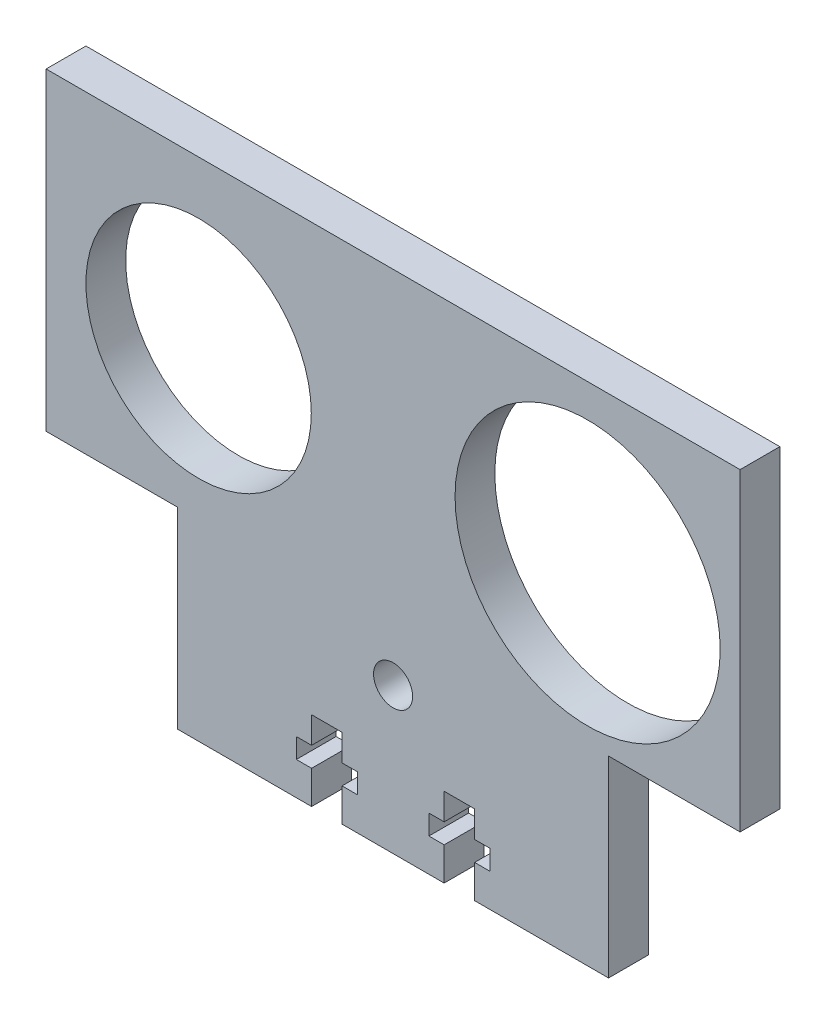
SolidWorks part; units mm, degrees
material "ABS"
ref_plane "Front Plane" through (0, 0, 0) normal (0, 0, 1) x (1, 0, 0)
ref_plane "Top Plane" through (0, 0, 0) normal (0, 1, 0) x (1, 0, 0)
ref_plane "Right Plane" through (0, 0, 0) normal (1, 0, 0) x (0, 0, -1)
sketch "Sketch1" plane through (0, 0, 0) normal (0, 0, 1) x (1, 0, 0)
  line L0 (0, 0) -> (-29.3449, 29.3449) construction
  line L1 (0, 0) -> (0, 54.3449) construction
  line L2 (-32.5, 7) -> (-32.5, -22)
  line L3 (-32.5, -22) -> (32.5, -22)
  line L4 (32.5, 7) -> (52.3449, 7)
  line L5 (0, 0) -> (0, -22) construction
  line L6 (52.3449, 7) -> (52.3449, 54.3449)
  line L7 (0, 0) -> (29.3449, 29.3449) construction
  line L10 (-32.5, 7) -> (-52.3449, 7)
  line L11 (-52.3449, 7) -> (-52.3449, 54.3449)
  line L12 (-52.3449, 54.3449) -> (52.3449, 54.3449)
  line L13 (32.5, 7) -> (32.5, -22)
  circle A0 centre (0, 0) radius 2.95
  circle A1 centre (-29.3449, 29.3449) radius 17
  circle A2 centre (29.3449, 29.3449) radius 20
  point P16 (0, 54.3449)
  dimension "D1" = 5.9
  dimension "D9" = 34
  dimension "D10" = 40
  dimension "D2" = 41.5
  dimension "D4" = 45
  dimension "D5" = 22
  dimension "D6" = 65
  dimension "D7" = 29
  dimension "D8" = 23
  dimension "D3" = 25
  dimension "D11" = 45
extrude "Boss-Extrude1" add sketch "Sketch1" along normal blind 6
sketch "Sketch3" plane through (0, 0, 6) normal (0, 0, 1) x (1, 0, 0)
  line L0 (-32.5, -22) -> (32.5, -22) construction
  line L1 (-12.3, -22) -> (-7.7, -22)
  line L2 (-12.3, -22) -> (-12.3, -17)
  line L3 (-12.3, -10) -> (-7.7, -10)
  line L4 (-7.7, -22) -> (-7.7, -17)
  line L5 (0, 0) -> (0, -22) construction
  line L6 (-7.7, -14) -> (-5.4, -14)
  line L7 (-14.6, -14) -> (-12.3, -14)
  line L8 (-14.6, -14) -> (-14.6, -17)
  line L9 (-14.6, -17) -> (-12.3, -17)
  line L10 (-5.4, -14) -> (-5.4, -17)
  line L11 (-12.3, -14) -> (-12.3, -10)
  line L12 (-7.7, -17) -> (-5.4, -17)
  line L13 (-7.7, -14) -> (-7.7, -10)
  line L14 (7.7, -14) -> (7.7, -10)
  line L15 (7.7, -17) -> (5.4, -17)
  line L16 (12.3, -14) -> (12.3, -10)
  line L17 (5.4, -14) -> (5.4, -17)
  line L18 (14.6, -17) -> (12.3, -17)
  line L19 (14.6, -14) -> (14.6, -17)
  line L20 (14.6, -14) -> (12.3, -14)
  line L21 (7.7, -14) -> (5.4, -14)
  line L22 (7.7, -22) -> (7.7, -17)
  line L23 (12.3, -10) -> (7.7, -10)
  line L24 (12.3, -22) -> (12.3, -17)
  line L25 (12.3, -22) -> (7.7, -22)
  point P6 (-10, -10)
  point P18 (-13.45, -17)
  dimension "D1" = 4.6
  dimension "D2" = 10
  dimension "D3" = 12
  dimension "D4" = 9.2
  dimension "D5" = 3
  dimension "D6" = 5
extrude "Cut-Extrude2" cut sketch "Sketch3" against normal through all
equation "\"smallPulleyTeeth\"= 15"
equation "\"largePulleyTeeth\"= 30"
equation "\"eighthThick\"= 2.9mm"
equation "\"sixteenthThick\" = 1.7mm"
equation "\"quarterThick\"=6.0mm"
equation "\"OD\" = 146mm"
equation "\"puckAngle\" = 60.5deg"
equation "\"puckDiam\" = 76.5mm"
equation "\"axlePress\" = 5.9mm"
equation "\"D1@Sketch1\"=\"axlePress\""
equation "\"D1@Boss-Extrude1\"=\"quarterThick\""
equation "\"press\" = 0.2mm"
equation "\"wheelClear\" = 0.3mm"
equation "\"10-32clear\" = 4.8mm"
equation "\"D1@Sketch3\"=\"10-32clear\" - \"press\""
equation "\"6-32clear\" = 3.3mm"
equation "\"8-32clear\" = 4.0mm"
equation "\"wheelHeight\" = 22mm"
equation "\"D5@Sketch1\"=\"wheelHeight\""
equation "\"D7@Sketch1\"=\"eighthThick\"*10"
equation "\"4-40clear\" = 3.0mm"
equation "\"wheelWell\" = 65mm"
equation "\"D6@Sketch1\"=\"wheelWell\""
